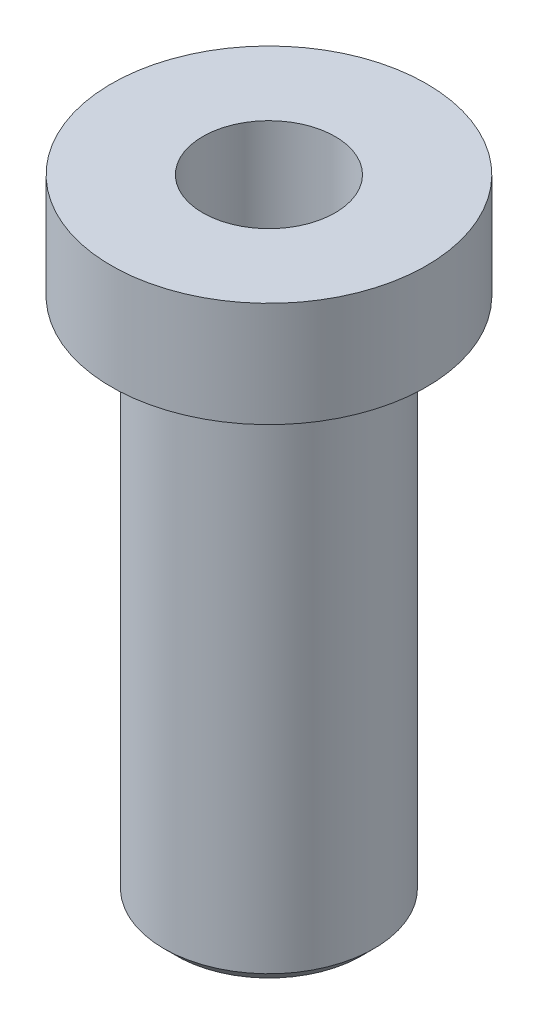
SolidWorks part; units mm, degrees
ref_plane "Front Plane" through (0, 0, 0) normal (0, 0, 1) x (1, 0, 0)
ref_plane "Top Plane" through (0, 0, 0) normal (0, 1, 0) x (1, 0, 0)
ref_plane "Right Plane" through (0, 0, 0) normal (1, 0, 0) x (0, 0, -1)
sketch "Sketch1" plane through (0, 0, 0) normal (0, 0, 1) x (1, 0, 0)
  line L0 (0, 0) -> (0, 3)
  line L1 (0, 3) -> (0.75, 3)
  line L2 (0.75, 3) -> (0.75, 2.5)
  line L3 (0.75, 2.5) -> (0.5, 2.5)
  line L4 (0.5, 2.5) -> (0.5, 0)
  line L5 (0.5, 0) -> (0, 0)
  dimension "D1" = 3
  dimension "D2" = 0.5
  dimension "D3" = 0.75
  dimension "D4" = 0.5
revolve "Revolve1" add sketch "Sketch1" angle 360 about L0
sketch "Sketch2" plane through (0, 3, 0) normal (0, 1, 0) x (1, 0, 0)
  circle A0 centre (0, 0) radius 0.315
  dimension "D1" = 0.63
extrude "Cut-Extrude1" cut sketch "Sketch2" against normal through all
chamfer "Chamfer1" distance 0.06 angle 45 1 edges at (0, 0, -0.5)
